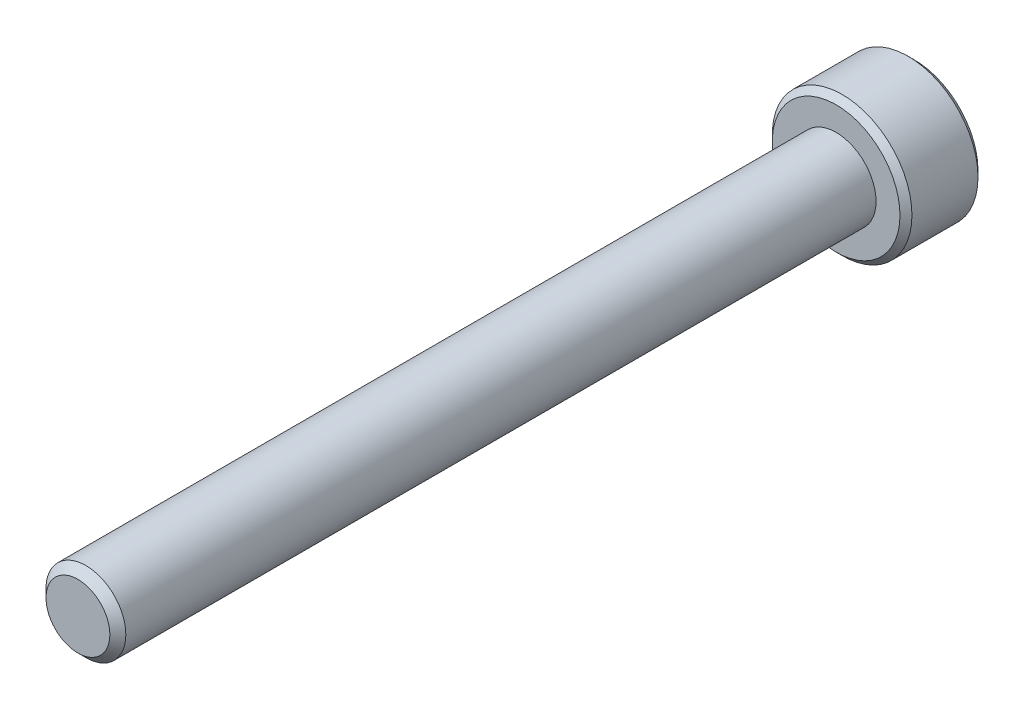
SolidWorks part; units mm, degrees
material "AISI 304"
ref_plane "前视基准面" through (0, 0, 0) normal (0, 0, 1) x (1, 0, 0)
ref_plane "上视基准面" through (0, 0, 0) normal (0, 1, 0) x (1, 0, 0)
ref_plane "右视基准面" through (0, 0, 0) normal (1, 0, 0) x (0, 0, -1)
sketch "草图1" plane through (0, 0, 0) normal (0, 0, 1) x (1, 0, 0)
  circle A0 centre (0, 0) radius 3.5
  dimension "D1" = 7
extrude "凸台-拉伸1" add sketch "草图1" along normal blind 3.91
sketch "草图2" plane through (0, 0, 3.91) normal (0, 0, 1) x (1, 0, 0)
  circle A0 centre (0, 0) radius 2
  dimension "D1" = 4
extrude "凸台-拉伸2" add sketch "草图2" along normal blind 38
sketch "草图3" plane through (0, 0, 0) normal (0, 0, -1) x (-1, 0, 0)
  line L1 (0, 1.7609) -> (-1.525, 0.8805)
  line L2 (-1.525, 0.8805) -> (-1.525, -0.8805)
  line L3 (-1.525, -0.8805) -> (0, -1.7609)
  line L4 (0, -1.7609) -> (1.525, -0.8805)
  line L5 (1.525, -0.8805) -> (1.525, 0.8805)
  line L6 (1.525, 0.8805) -> (0, 1.7609)
  circle A0 centre (0, 0) radius 1.525 construction
  dimension "D1" = 3.05
extrude "切除-拉伸1" cut sketch "草图3" against normal blind 2
chamfer "倒角1" distance 0.4 angle 45 1 edges at (2, 0, 41.91)
chamfer "倒角2" distance 0.3 angle 45 2 edges at (3.5, 0, 3.91) (3.5, 0, 0)
